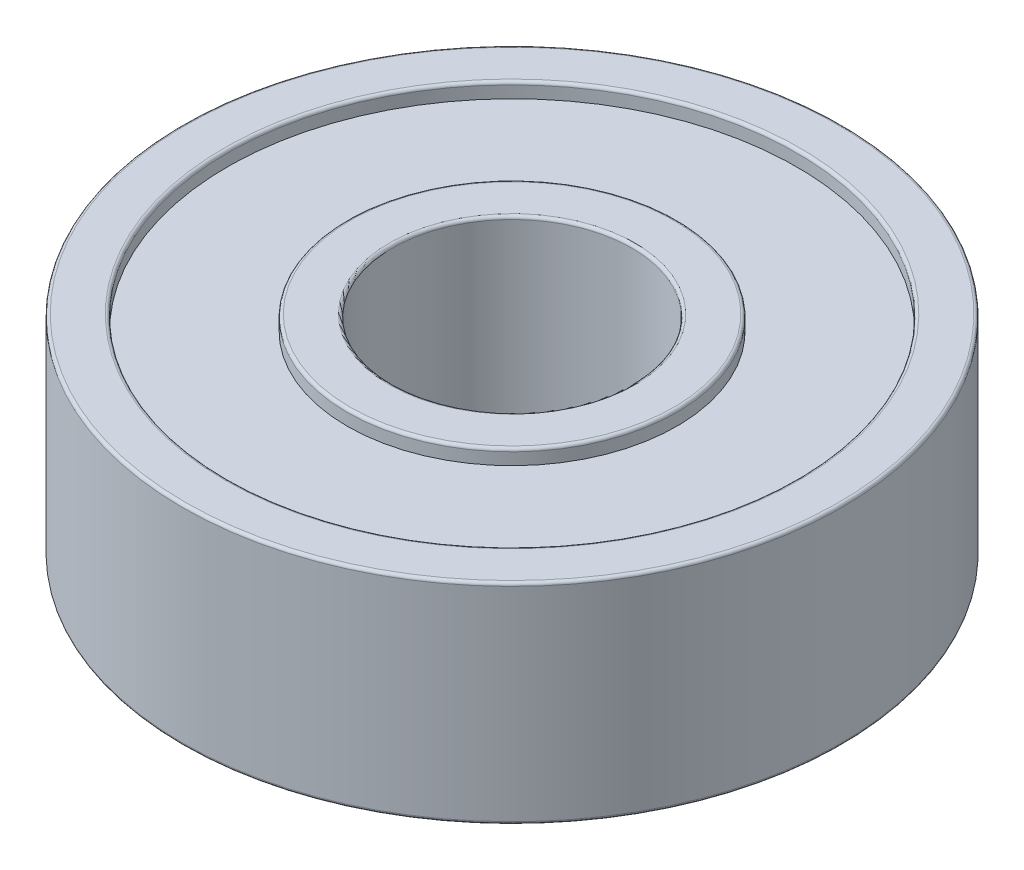
SolidWorks part; units mm, degrees
ref_plane "Front Plane" through (0, 0, 0) normal (0, 0, 1) x (1, 0, 0)
ref_plane "Top Plane" through (0, 0, 0) normal (0, 1, 0) x (1, 0, 0)
ref_plane "Right Plane" through (0, 0, 0) normal (1, 0, 0) x (0, 0, -1)
sketch "Sketch1" plane through (0, 0, 0) normal (0, 1, 0) x (1, 0, 0)
  circle A0 centre (0, 0) radius 11
  circle A1 centre (0, 0) radius 4
  dimension "D1" = 22
  dimension "D2" = 8
extrude "Boss-Extrude1" add sketch "Sketch1" along normal blind 3.5 and the other way blind 3.5
sketch "Sketch2" plane through (0, 3.5, 0) normal (0, 1, 0) x (1, 0, 0)
  circle A0 centre (0, 0) radius 5.5
  circle A1 centre (0, 0) radius 9.5
  circle A2 centre (0, 0) radius 4 construction
  circle A3 centre (0, 0) radius 11 construction
  dimension "D1" = 1.5
  dimension "D2" = 1.5
extrude "Cut-Extrude1" cut sketch "Sketch2" against normal blind 0.5
fillet "Fillet2" radius 0.1 4 edges at (0, 3.5, 11) (0, 3.5, 9.5) (0, 3.5, 4) (0, 3.5, 5.5)
mirror "Mirror4" about plane through (0, 0, 0) normal (0, 1, 0) of "Cut-Extrude1"
fillet "Fillet3" radius 0.1 4 edges at (0, -3.5, 4) (0, -3.5, 5.5) (0, -3.5, 9.5) (0, -3.5, 11)
